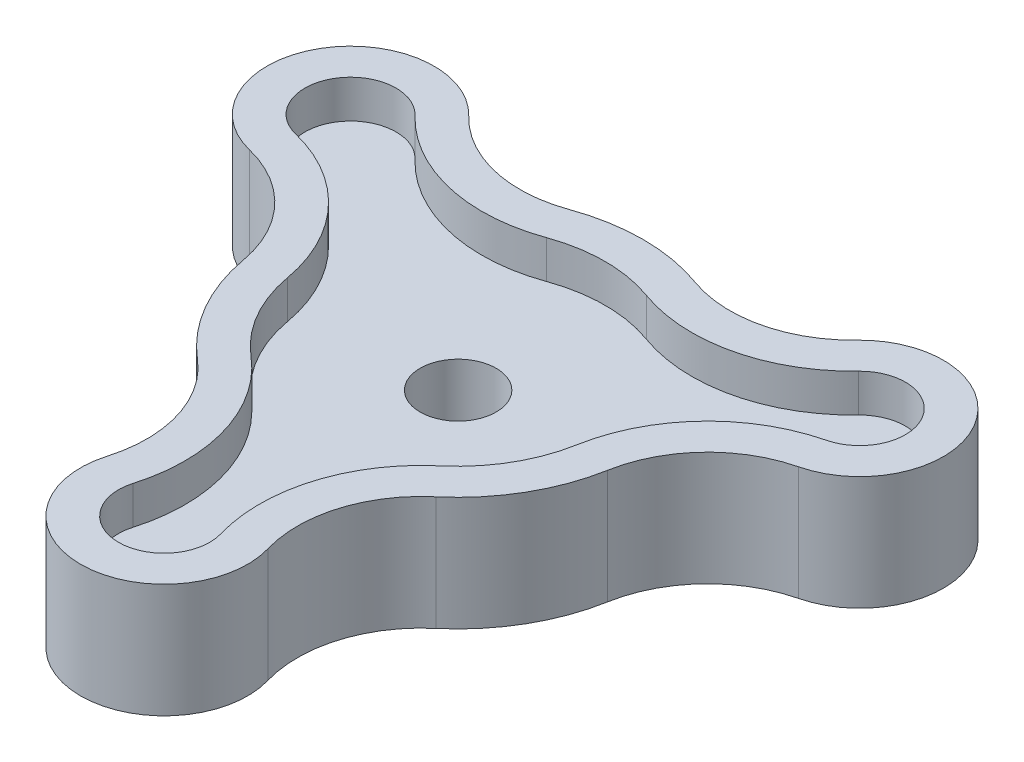
SolidWorks part; units mm, degrees
ref_plane "Front Plane" through (0, 0, 0) normal (0, 0, 1) x (1, 0, 0)
ref_plane "Top Plane" through (0, 0, 0) normal (0, 1, 0) x (1, 0, 0)
ref_plane "Right Plane" through (0, 0, 0) normal (1, 0, 0) x (0, 0, -1)
sketch "Sketch1" plane through (0, 0, 0) normal (0, 1, 0) x (1, 0, 0)
  line L1 (0, 0) -> (57.15, 0)
  line L2 (0, 0) -> (0, -57.15)
  line L3 (0, -57.15) -> (57.15, -57.15)
  line L4 (57.15, 0) -> (57.15, -57.15)
  dimension "D2" = 57.15
extrude "Boss-Extrude1" add sketch "Sketch1" along normal blind 9.525
sketch "Sketch5" plane through (0, 9.525, 0) normal (0, 1, 0) x (1, 0, 0)
  line L0 (49.8475, -10.1525) -> (28.575, -46.9975) construction
  line L1 (28.575, -46.9975) -> (7.3025, -10.1525) construction
  line L2 (7.3025, -10.1525) -> (49.8475, -10.1525) construction
  line L3 (28.575, -10.1525) -> (28.575, -46.9975) construction
  line L4 (57.15, -28.575) -> (0, -28.575) construction
  line L5 (57.15, -57.15) -> (57.15, 0) construction
  line L6 (0, 0) -> (0, -57.15) construction
  line L7 (28.575, -57.15) -> (28.575, 0) construction
  line L8 (0, -57.15) -> (57.15, -57.15) construction
  line L9 (57.15, 0) -> (0, 0) construction
  circle A0 centre (28.575, -22.4342) radius 12.2817
  arc A2 (50.753, -13.8533) -> (47.0952, -7.5179) centre (49.8475, -10.1525) ccw
  arc A3 (10.0548, -7.5179) -> (6.397, -13.8533) centre (7.3025, -10.1525) ccw
  circle A4 centre (28.575, -22.4342) radius 3.302
  arc A5 (36.4931, -31.8227) -> (32.2328, -45.9313) centre (45.2032, -42.1503) ccw
  arc A6 (50.753, -13.8533) -> (40.6647, -24.5971) centre (53.9638, -26.9765) ccw
  arc A7 (24.9172, -45.9313) -> (20.6569, -31.8227) centre (11.9468, -42.1503) ccw
  arc A9 (10.0548, -7.5179) -> (24.4033, -10.8827) centre (19.8144, 1.8244) ccw
  arc A10 (32.7467, -10.8827) -> (47.0952, -7.5179) centre (37.3356, 1.8244) ccw
  arc A11 (16.4853, -24.5971) -> (6.397, -13.8533) centre (3.1862, -26.9765) ccw
  arc A13 (24.9172, -45.9313) -> (32.2328, -45.9313) centre (28.575, -46.9975) ccw
  point P17 (28.575, -28.575)
  point P49 (21.8691, -45.0427)
  point P51 (28.575, -46.9975)
  point P52 (35.2809, -45.0427)
  point P69 (28.575, -22.4342)
  point P71 (44.0317, -22.4342)
  dimension "D2" = 24.5634
  dimension "D3" = 3.81
  dimension "D4" = 6.604
  dimension "D5" = 27.0205
  dimension "D1" = 42.545
  dimension "D6" = 7.3155
  dimension "D7" = 19.7162
  dimension "D8" = 4.5423
extrude "Cut-Extrude1" cut sketch "Sketch5" against normal blind 3.175 contours A7 A13 A5 A0 | A0 A4 | A4 | A11 A0 A9 A3 | A10 A0 A6 A2
sketch "Sketch7" plane through (0, 9.525, 0) normal (0, 1, 0) x (1, 0, 0)
  arc A38 (12.3483, -5.3224) -> (5.6425, -16.9373) centre (7.3025, -10.1525) ccw
  arc A39 (13.3599, -25.1563) -> (5.6425, -16.9373) centre (3.1862, -26.9765) ccw
  arc A40 (13.3599, -25.1563) -> (18.61, -34.2497) centre (28.575, -22.4342) ccw
  arc A41 (21.8691, -45.0427) -> (18.61, -34.2497) centre (11.9468, -42.1503) ccw
  arc A42 (21.8691, -45.0427) -> (35.2809, -45.0427) centre (28.575, -46.9975) ccw
  arc A43 (38.54, -34.2497) -> (35.2809, -45.0427) centre (45.2032, -42.1503) ccw
  arc A44 (38.54, -34.2497) -> (43.7901, -25.1563) centre (28.575, -22.4342) ccw
  arc A45 (51.5075, -16.9373) -> (43.7901, -25.1563) centre (53.9638, -26.9765) ccw
  arc A46 (51.5075, -16.9373) -> (44.8017, -5.3224) centre (49.8475, -10.1525) ccw
  arc A47 (33.8251, -7.8964) -> (44.8017, -5.3224) centre (37.3356, 1.8244) ccw
  arc A48 (33.8251, -7.8964) -> (23.3249, -7.8964) centre (28.575, -22.4342) ccw
  arc A49 (12.3483, -5.3224) -> (23.3249, -7.8964) centre (19.8144, 1.8244) ccw
  arc A50 (12.3483, -5.3224) -> (5.6425, -16.9373) centre (7.3025, -10.1525) ccw
  arc A51 (13.3599, -25.1563) -> (5.6425, -16.9373) centre (3.1862, -26.9765) ccw
  arc A52 (13.3599, -25.1563) -> (18.61, -34.2497) centre (28.575, -22.4342) ccw
  arc A53 (21.8691, -45.0427) -> (18.61, -34.2497) centre (11.9468, -42.1503) ccw
  arc A54 (21.8691, -45.0427) -> (35.2809, -45.0427) centre (28.575, -46.9975) ccw
  arc A55 (38.54, -34.2497) -> (35.2809, -45.0427) centre (45.2032, -42.1503) ccw
  arc A56 (38.54, -34.2497) -> (43.7901, -25.1563) centre (28.575, -22.4342) ccw
  arc A57 (51.5075, -16.9373) -> (43.7901, -25.1563) centre (53.9638, -26.9765) ccw
  arc A58 (51.5075, -16.9373) -> (44.8017, -5.3224) centre (49.8475, -10.1525) ccw
  arc A59 (33.8251, -7.8964) -> (44.8017, -5.3224) centre (37.3356, 1.8244) ccw
  arc A60 (33.8251, -7.8964) -> (23.3249, -7.8964) centre (28.575, -22.4342) ccw
  arc A61 (12.3483, -5.3224) -> (23.3249, -7.8964) centre (19.8144, 1.8244) ccw
  line M13 (0, 0) -> (0, -57.15)
  line M14 (0, -57.15) -> (57.15, -57.15)
  line M15 (57.15, -57.15) -> (57.15, 0)
  line M16 (57.15, 0) -> (0, 0)
  dimension "D1" = 3.175
extrude "Cut-Extrude2" cut sketch "Sketch7" against normal blind 9.652 contours A50 A61 A60 A59 A58 A57 A56 A55 A54 A53 A52 A51 M16 M13 M14 M15
sketch "Sketch10" plane through (0, 6.35, 0) normal (0, 1, 0) x (1, 0, 0)
  circle A0 centre (28.575, -22.4342) radius 3.175
  arc A1 (38.54, -34.2497) -> (43.7901, -25.1563) centre (28.575, -22.4342) ccw construction
  dimension "D1" = 6.35
extrude "Cut-Extrude4" cut sketch "Sketch10" against normal through all
equation "\"FACTOR_OF_SIZE\"=1.675"
equation "\"factor\"=1"
